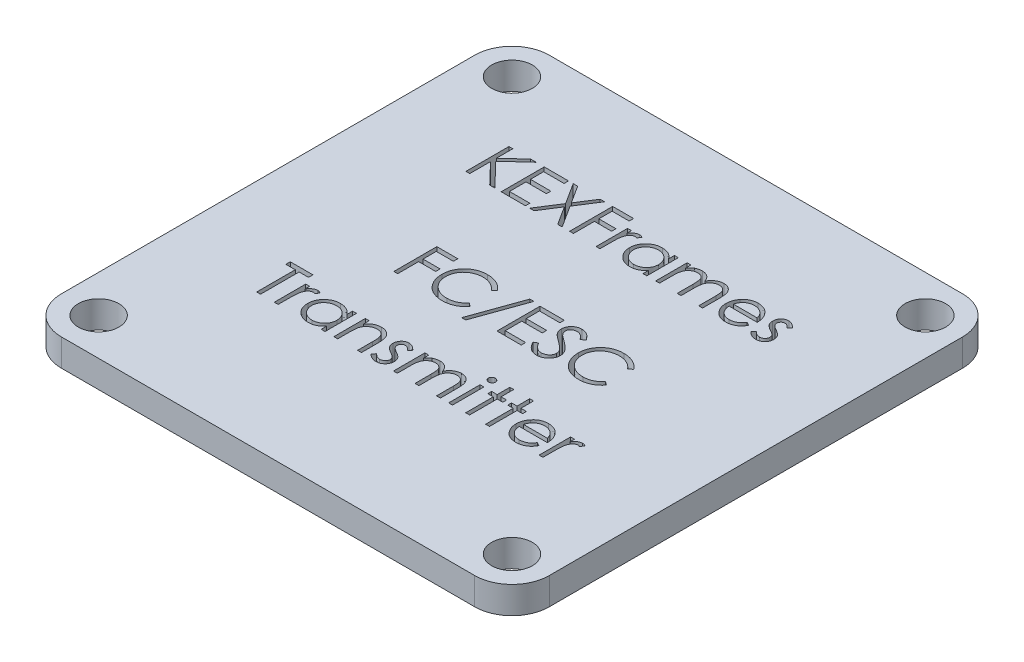
SolidWorks part; units mm, degrees
ref_plane "Front Plane" through (0, 0, 0) normal (0, 0, 1) x (1, 0, 0)
ref_plane "Top Plane" through (0, 0, 0) normal (0, 1, 0) x (1, 0, 0)
ref_plane "Right Plane" through (0, 0, 0) normal (1, 0, 0) x (0, 0, -1)
sketch "Sketch1" plane through (0, 0, 0) normal (0, 1, 0) x (1, 0, 0)
  line L1 (-15.25, 15.25) -> (15.25, 15.25) construction
  line L2 (-15.25, 15.25) -> (-15.25, -15.25) construction
  line L3 (-15.25, -15.25) -> (15.25, -15.25) construction
  line L4 (15.25, 15.25) -> (15.25, -15.25) construction
  line L5 (-15.25, 15.25) -> (15.25, -15.25) construction
  line L6 (-15.25, -15.25) -> (15.25, 15.25) construction
  line L7 (-18, -18) -> (18, -18)
  line L8 (-18, -18) -> (-18, 18)
  line L9 (-18, 18) -> (18, 18)
  line L10 (18, -18) -> (18, 18)
  line L11 (-18, -18) -> (18, 18) construction
  line L12 (-18, 18) -> (18, -18) construction
  circle A0 centre (-15.25, -15.25) radius 1.5
  circle A1 centre (15.25, -15.25) radius 1.5
  circle A2 centre (-15.25, 15.25) radius 1.5
  circle A3 centre (15.25, 15.25) radius 1.5
  arc A4 (-15.25, 18) -> (-18, 15.25) centre (-15.25, 15.25) ccw
  arc A5 (18, 15.25) -> (15.25, 18) centre (15.25, 15.25) ccw
  arc A6 (-15.25, -18) -> (-18, -15.25) centre (-15.25, -15.25) cw
  arc A7 (18, -15.25) -> (15.25, -18) centre (15.25, -15.25) cw
  point P0 (0, 0)
  point P7 (0, 0)
  dimension "D5" = 3
  dimension "D6" = 3
  dimension "D7" = 3
  dimension "D8" = 3
  dimension "D1" = 30.5
  dimension "D2" = 30.5
  dimension "D3" = 36
  dimension "D4" = 36
extrude "Boss-Extrude1" add sketch "Sketch1" along normal blind 2 contours A6 L7 L10 A5 L9 A4 L8 A3 A2 A1 A0
sketch "Sketch3" plane through (0, 2, 0) normal (0, 1, 0) x (1, 0, 0)
  text T0 "KEXFrames"
  text T1 "FC/ESC"
  text T2 "Transmitter\r\n"
  point P1 (-11.3077, 7.4986)
  point P3 (-1.7728, -3.2342)
  point P4 (-1.9645, -2.0843)
  point P5 (0, 0)
  point P6 (0, 0)
  point P7 (-2.5394, -1.5093)
  point P8 (-7.2829, -2.1322)
  point P9 (-7.235, -0.9822)
  point P10 (0, 0)
  point P11 (0, 0)
  point P12 (-7.5704, -1.5572)
  point P14 (-10.1099, -8.0735)
  point P15 (0, 0)
  point P16 (0, 0)
  point P17 (-11.6431, -7.9298)
extrude "Cut-Extrude2" cut sketch "Sketch3" against normal through all
